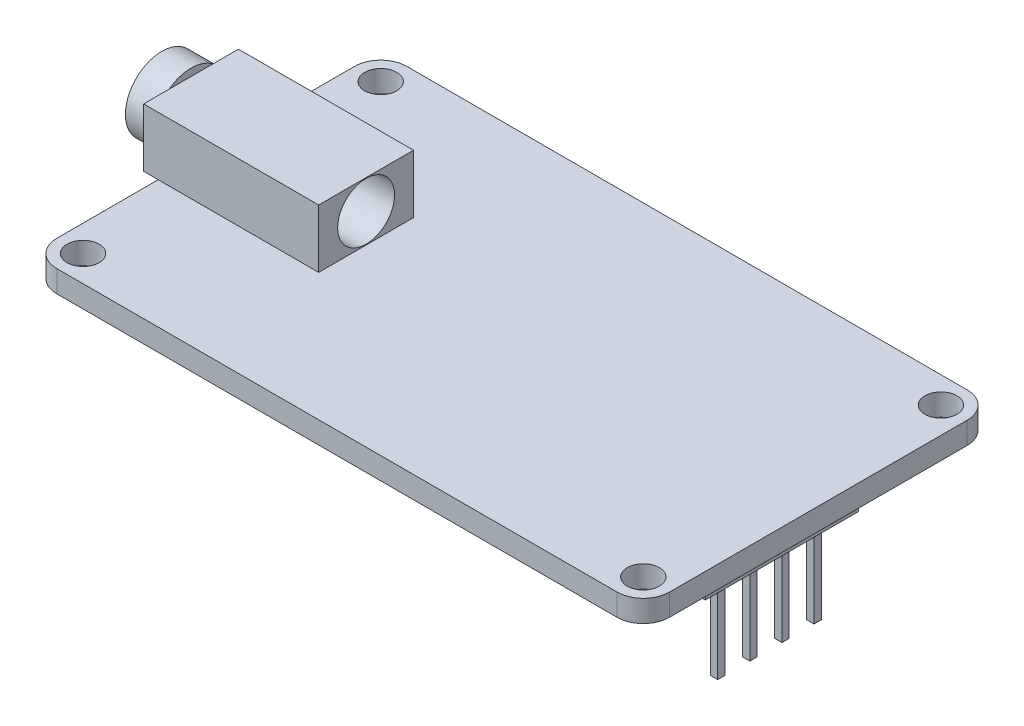
SolidWorks part; units mm, degrees
ref_plane "Plan de face" through (0, 0, 0) normal (0, 0, 1) x (1, 0, 0)
ref_plane "Plan de dessus" through (0, 0, 0) normal (0, 1, 0) x (1, 0, 0)
ref_plane "Plan de droite" through (0, 0, 0) normal (1, 0, 0) x (0, 0, -1)
sketch "Sketch1" plane through (0, 0, 0) normal (0, 1, 0) x (1, 0, 0)
  line L1 (-1.8, 0) -> (-40.2, 0)
  line L2 (0, 1.8) -> (0, 22.2)
  line L3 (-1.8, 24) -> (-40.2, 24)
  line L4 (-42, 1.8) -> (-42, 22.2)
  arc A0 (-40.2, 0) -> (-42, 1.8) centre (-40.2, 1.8) cw
  arc A1 (-1.8, 0) -> (0, 1.8) centre (-1.8, 1.8) ccw
  arc A2 (0, 22.2) -> (-1.8, 24) centre (-1.8, 22.2) ccw
  arc A3 (-40.2, 24) -> (-42, 22.2) centre (-40.2, 22.2) ccw
  circle A4 centre (-40.2, 1.8) radius 1.1
  circle A5 centre (-1.8, 1.8) radius 1.1
  circle A6 centre (-1.8, 22.2) radius 1.1
  circle A7 centre (-40.2, 22.2) radius 1.1
  point P9 (0, 0)
  point P12 (0, 24)
  point P15 (-42, 24)
  dimension "D3" = 1.8
  dimension "D4" = 2.2
  dimension "D5" = 2.2
  dimension "D6" = 2.2
  dimension "D7" = 2.2
  dimension "D1" = 24
  dimension "D2" = 42
extrude "Boss-Extrude1" add sketch "Sketch1" along normal blind 1.5
sketch "Sketch2" plane through (0, 1.5, 0) normal (0, 1, 0) x (1, 0, 0)
  line L0 (-40.2, 0) -> (-1.8, 0) construction
  line L1 (-31, 15.25) -> (-43, 15.25)
  line L2 (-31, 15.25) -> (-31, 8.75)
  line L3 (-31, 8.75) -> (-43, 8.75)
  line L4 (-43, 15.25) -> (-43, 8.75)
  line L8 (-42, 22.2) -> (-42, 1.8) construction
  dimension "D1" = 6.5
  dimension "D2" = 8.75
  dimension "D3" = 12
  dimension "D4" = 11
extrude "Boss-Extrude2" add sketch "Sketch2" along normal blind 4
sketch "Sketch5" plane through (-43, 0, 0) normal (-1, 0, 0) x (0, 0, 1)
  line L0 (-15.25, 5.5) -> (-8.75, 1.5) construction
  line L1 (-8.75, 5.5) -> (-15.25, 1.5) construction
  circle A0 centre (-12, 3.5) radius 2.5
  dimension "D1" = 5
extrude "Boss-Extrude3" add sketch "Sketch5" along normal blind 2
sketch "Sketch6" plane through (-45, 0, 0) normal (-1, 0, 0) x (0, 0, 1)
  circle A0 centre (-12, 3.5) radius 1.95
  dimension "D1" = 3.9
extrude "Cut-Extrude1" cut sketch "Sketch6" against normal blind 15.0276
sketch "Sketch8" plane through (0, 0, 0) normal (0, -1, 0) x (1, 0, 0)
  line L0 (0, -1.8) -> (0, -22.2) construction
  line L1 (-2.5, -6.75) -> (-4.7, -6.75)
  line L2 (-2.5, -6.75) -> (-2.5, -17.25)
  line L3 (-2.5, -17.25) -> (-4.7, -17.25)
  line L4 (-4.7, -6.75) -> (-4.7, -17.25)
  line L5 (-40.2, 0) -> (-1.8, 0) construction
  dimension "D1" = 2.2
  dimension "D2" = 10.5
  dimension "D3" = 2.5
  dimension "D4" = 6.75
extrude "Boss-Extrude4" add sketch "Sketch8" along normal blind 2.7
sketch "Sketch9" plane through (0, -2.7, 0) normal (0, -1, 0) x (1, 0, 0)
  line L0 (-2.5, -6.75) -> (-4.7, -6.75) construction
  line L1 (-3.85, -8.45) -> (-3.35, -8.45)
  line L2 (-3.85, -8.45) -> (-3.85, -8.95)
  line L3 (-3.85, -8.95) -> (-3.35, -8.95)
  line L4 (-3.35, -8.45) -> (-3.35, -8.95)
  line L5 (-4.7, -6.75) -> (-4.7, -17.25) construction
  dimension "D1" = 0.5
  dimension "D2" = 0.5
  dimension "D3" = 1.7
  dimension "D4" = 0.85
extrude "Boss-Extrude5" add sketch "Sketch9" along normal blind 6 contours L4 L3 L2 L1
pattern_linear "LPattern1" count 4 spacing 2.2 along (0, 0, -1) of "Boss-Extrude5"
